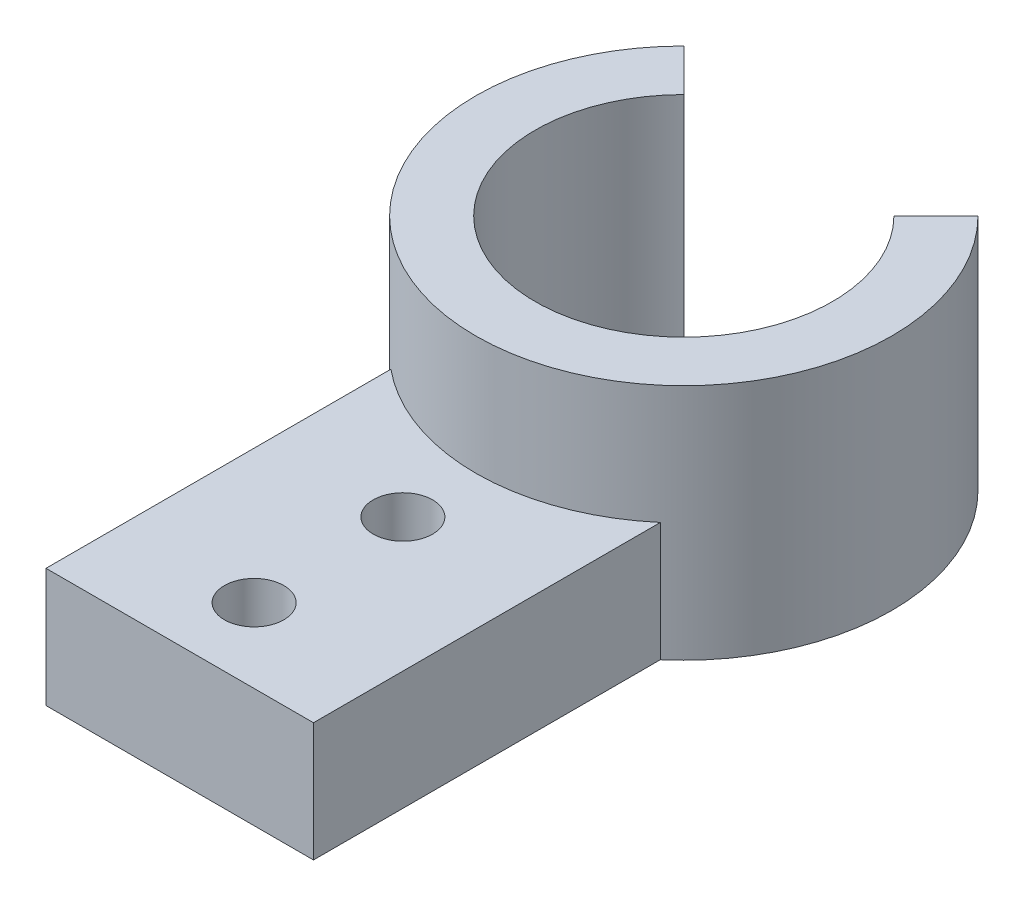
SolidWorks part; units mm, degrees
ref_plane "Front Plane" through (0, 0, 0) normal (0, 0, 1) x (1, 0, 0)
ref_plane "Top Plane" through (0, 0, 0) normal (0, 1, 0) x (1, 0, 0)
ref_plane "Right Plane" through (0, 0, 0) normal (1, 0, 0) x (0, 0, -1)
sketch "Sketch1" plane through (0, 0, 0) normal (0, 1, 0) x (1, 0, 0)
  circle A0 centre (0, 0) radius 5
  circle A1 centre (0, 0) radius 7
  dimension "D1" = 10
  dimension "D2" = 14
extrude "Boss-Extrude1" add sketch "Sketch1" along normal blind 8
sketch "Sketch2" plane through (0, 8, 0) normal (0, 1, 0) x (1, 0, 0)
  line L1 (0, 0) -> (-4.9497, 4.9497)
  line L2 (-4.9497, 4.9497) -> (-8.5264, 8.5264)
  line L3 (-8.5264, 8.5264) -> (8.5264, 8.5264)
  line L4 (8.5264, 8.5264) -> (0, 0)
  circle A0 centre (0, 0) radius 7 construction
extrude "Cut-Extrude1" cut sketch "Sketch2" against normal blind 8
sketch "Sketch5" plane through (0, 0, 0) normal (0, 1, 0) x (1, 0, 0)
  line L0 (-4.4603, -7) -> (4.5397, -7)
  line L1 (-4.4603, -7) -> (-4.4603, -17)
  line L2 (-4.4603, -17) -> (4.5397, -17)
  line L3 (4.5397, -17) -> (4.5397, -7)
  point P3 (0.0397, -7)
  dimension "D1" = 9
  dimension "D2" = 10
extrude "Boss-Extrude2" add sketch "Sketch5" along normal blind 4 separate body
sketch "Sketch6" plane through (0, 0, 7) normal (0, 0, -1) x (-1, 0, 0)
  line L1 (-4.5397, 4) -> (4.4603, 4)
  line L2 (-4.5397, 4) -> (-4.5397, 0)
  line L3 (-4.5397, 0) -> (4.4603, 0)
  line L4 (4.4603, 4) -> (4.4603, 0)
extrude "Boss-Extrude4" add sketch "Sketch6" along normal up to surface (4.7405 mm away)
sketch "Sketch8" plane through (0, 4, 0) normal (0, 1, 0) x (1, 0, 0)
  line L0 (0.0518, -6.9998) -> (0.0397, -17) construction
  line L1 (-4.4603, -17) -> (4.5397, -17) construction
  line L2 (0.0427, -14.4999) -> (0.0488, -9.4999) construction
  arc A0 (-4.4603, -5.3949) -> (4.5397, -5.3284) centre (0, 0) ccw construction
  circle A2 centre (0.0488, -9.4999) radius 1
  circle A3 centre (0.0427, -14.4999) radius 1
  point P10 (0.0457, -11.9999)
  dimension "D3" = 2
  dimension "D4" = 2
  dimension "D1" = 10.0002
  dimension "D2" = 5
extrude "Cut-Extrude2" cut sketch "Sketch8" against normal blind 8
